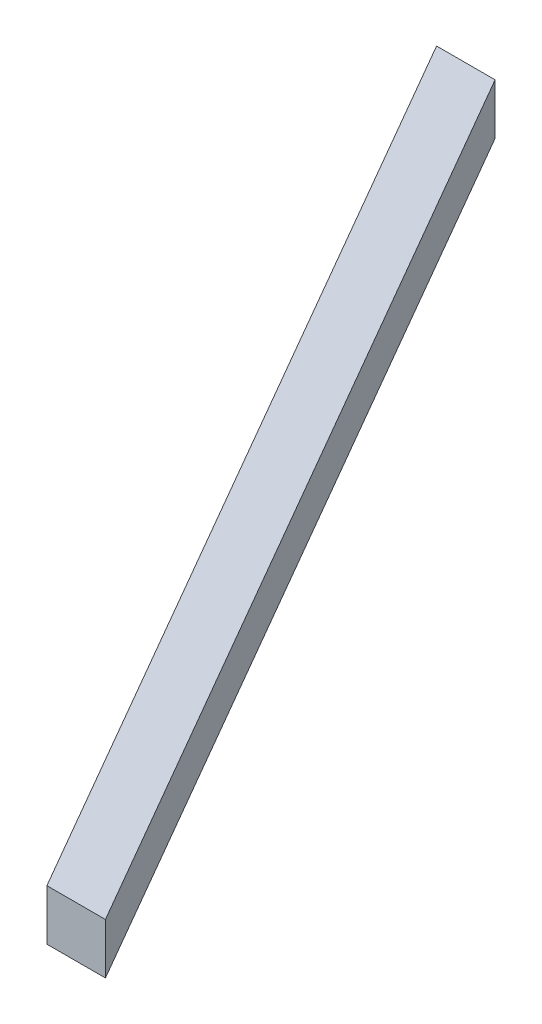
SolidWorks part; units mm, degrees
ref_plane "前视基准面" through (0, 0, 0) normal (0, 0, 1) x (1, 0, 0)
ref_plane "上视基准面" through (0, 0, 0) normal (0, 1, 0) x (1, 0, 0)
ref_plane "右视基准面" through (0, 0, 0) normal (1, 0, 0) x (0, 0, -1)
sketch "草图1" plane through (0, 0, 0) normal (0, 1, 0) x (1, 0, 0)
  line L0 (-600, -200) -> (600, -200) construction
  line L1 (270, -200) -> (480, -563.7307)
  line L5 (480, -563.7307) -> (503.094, -563.7307)
  line L6 (503.094, -563.7307) -> (293.094, -200)
  line L8 (270, -200) -> (293.094, -200)
  point P2 (0, -200)
  point P5 (270, -200)
  dimension "D1" = 1200
  dimension "D2" = 200
  dimension "D3" = 870
  dimension "D4" = 20
  dimension "D5" = 420
  dimension "D6" = 60
extrude "凸台-拉伸1" add sketch "草图1" along normal blind 20 contours L1 L5 L6 L8
